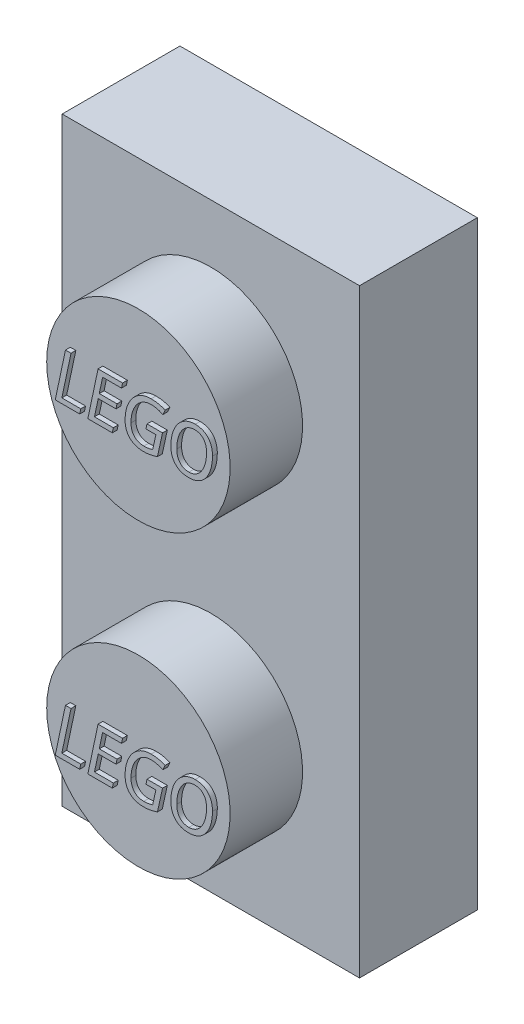
SolidWorks part; units mm, degrees
ref_plane "Front Plane" through (0, 0, 0) normal (0, 0, 1) x (1, 0, 0)
ref_plane "Top Plane" through (0, 0, 0) normal (0, 1, 0) x (1, 0, 0)
ref_plane "Right Plane" through (0, 0, 0) normal (1, 0, 0) x (0, 0, -1)
sketch "Sketch1" plane through (0, 0, 0) normal (0, 0, 1) x (1, 0, 0)
  line L1 (-3.9116, -7.8867) -> (3.9116, -7.8867)
  line L2 (-3.9116, -7.8867) -> (-3.9116, 7.8867)
  line L3 (-3.9116, 7.8867) -> (3.9116, 7.8867)
  line L4 (3.9116, -7.8867) -> (3.9116, 7.8867)
  line L5 (-3.9116, -7.8867) -> (3.9116, 7.8867) construction
  line L6 (-3.9116, 7.8867) -> (3.9116, -7.8867) construction
  point P0 (0, 0)
  dimension "D1" = 15.7734
  dimension "D2" = 7.8232
extrude "Boss-Extrude1" add sketch "Sketch1" along normal blind 3.0988
sketch "Sketch2" plane through (0, 0, 3.0988) normal (0, 0, 1) x (1, 0, 0)
  line L0 (-3.9116, 0) -> (3.9116, 0) construction
  line L1 (-3.9116, 7.8867) -> (-3.9116, -7.8867) construction
  line L2 (3.9116, -7.8867) -> (3.9116, 7.8867) construction
  line L3 (0, -7.8867) -> (0, 7.8867) construction
  line L4 (-3.9116, -7.8867) -> (3.9116, -7.8867) construction
  line L5 (3.9116, 7.8867) -> (-3.9116, 7.8867) construction
  line L6 (0, 7.8867) -> (0, 3.9434) construction
  line L8 (-3.9116, 3.3147) -> (3.9116, 3.3147) construction
  circle A0 centre (0, 3.9434) radius 2.413
  circle A1 centre (0, -3.9434) radius 2.413
  text T0 "LEGO" font "Open Sans" height 1.27
  dimension "D1" = 4.826
  dimension "D2" = 3.9434
  dimension "D3" = 4.572
extrude "Boss-Extrude2" add sketch "Sketch2" along normal blind 1.905 contours A1 | A0
sketch "Sketch3" plane through (0, 0, 5.0038) normal (0, 0, 1) x (1, 0, 0)
  line L0 (-3.9116, 0) -> (3.9116, 0) construction
  line L3 (0, -7.8867) -> (0, 7.8867) construction
  line L6 (0, 7.8867) -> (0, 3.9434) construction
  line L8 (-3.9116, 3.3147) -> (3.9116, 3.3147) construction
  text T0 "LEGO" font "Open Sans" height 1.27
  dimension "D2" = 3.9434
extrude "Boss-Extrude3" add sketch "Sketch3" along normal blind 0.127
sketch "Sketch4" plane through (0, 0, 5.0038) normal (0, 0, 1) x (1, 0, 0)
  line L0 (-3.9116, 0) -> (3.9116, 0) construction
  line L3 (0, -7.8867) -> (0, 7.8867) construction
  line L6 (0, 7.8867) -> (0, 3.9434) construction
  line L8 (-3.9116, -4.7799) -> (3.9116, -4.7799) construction
  text T0 "LEGO" font "Open Sans" height 1.27
  dimension "D2" = 3.9434
extrude "Boss-Extrude4" add sketch "Sketch4" along normal blind 0.127
sketch "Sketch5" plane through (0, 0, 0) normal (0, 0, -1) x (-1, 0, 0)
  line L0 (-3.9116, 7.8867) -> (3.9116, 7.8867) construction
  line L1 (-2.3876, -6.3627) -> (2.3876, -6.3627)
  line L2 (-2.3876, -6.3627) -> (-2.3876, 6.3627)
  line L3 (-2.3876, 6.3627) -> (2.3876, 6.3627)
  line L4 (2.3876, -6.3627) -> (2.3876, 6.3627)
  line L5 (-2.3876, -6.3627) -> (2.3876, 6.3627) construction
  line L6 (-2.3876, 6.3627) -> (2.3876, -6.3627) construction
  line L7 (3.9116, 7.8867) -> (3.9116, -7.8867) construction
  point P0 (0, 0)
  dimension "D1" = 1.524
  dimension "D2" = 1.524
extrude "Cut-Extrude1" cut sketch "Sketch5" against normal blind 2.54
sketch "Sketch6" plane through (0, 0, 2.54) normal (0, 0, -1) x (-1, 0, 0)
  line L0 (0, 0) -> (-2.3876, 0) construction
  line L1 (-2.3876, 6.3627) -> (-2.3876, -6.3627) construction
  line L2 (0, 0) -> (0, 6.3627) construction
  line L3 (2.3876, 6.3627) -> (-2.3876, 6.3627) construction
  circle A0 centre (0, 3.1813) radius 1.27
  circle A1 centre (0, -3.1813) radius 1.27
  dimension "D1" = 2.54
extrude "Cut-Extrude2" cut sketch "Sketch6" against normal blind 2.032
sketch "Sketch7" plane through (0, 0, 2.54) normal (0, 0, -1) x (-1, 0, 0)
  circle A0 centre (0, 0) radius 1.4859
  dimension "D1" = 2.9718
extrude "Boss-Extrude5" add sketch "Sketch7" along normal up to surface (2.54 mm away) contours A0 up to face at (0, 0, 0)
sketch "Sketch8" plane through (0, 0, 0) normal (0, 0, -1) x (-1, 0, 0)
  circle A0 centre (0, 0) radius 0.635
  dimension "D1" = 1.27
extrude "Cut-Extrude3" cut sketch "Sketch8" against normal up to surface (2.54 mm away) up to face at (1.4859, 0, 2.54)
